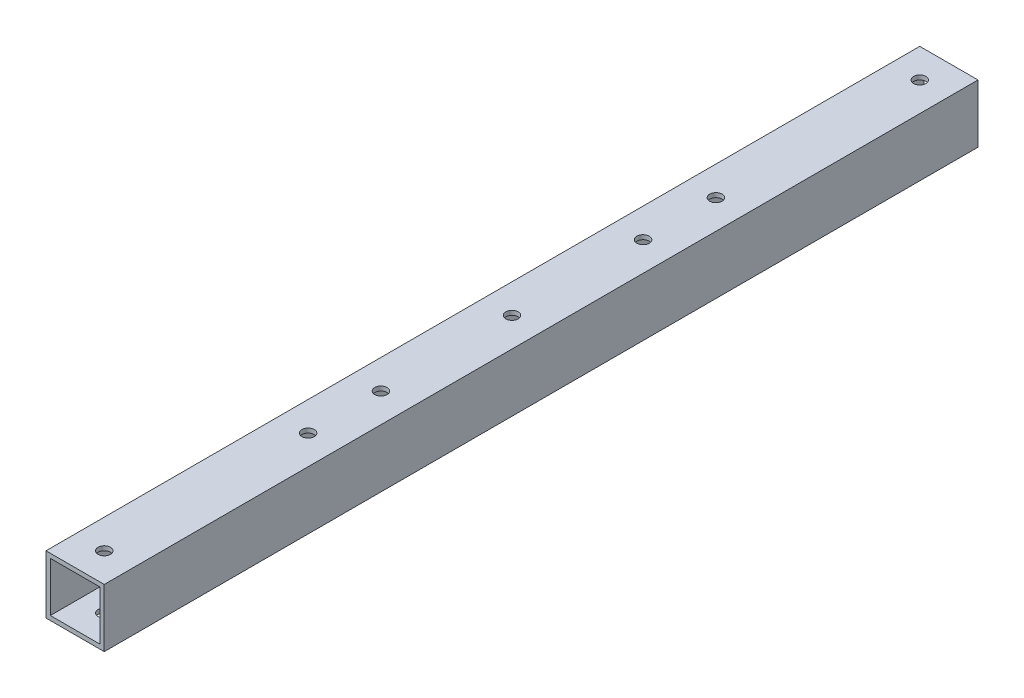
SolidWorks part; units mm, degrees
ref_plane "Front Plane" through (0, 0, 0) normal (0, 0, 1) x (1, 0, 0)
ref_plane "Top Plane" through (0, 0, 0) normal (0, 1, 0) x (1, 0, 0)
ref_plane "Right Plane" through (0, 0, 0) normal (1, 0, 0) x (0, 0, -1)
sketch "Sketch1" plane through (0, 0, 0) normal (0, 0, 1) x (1, 0, 0)
  line L0 (-8.5, -8.5) -> (8.5, -8.5)
  line L1 (-10, -10) -> (10, -10)
  line L2 (-10, -10) -> (-10, 10)
  line L3 (-10, 10) -> (10, 10)
  line L4 (10, -10) -> (10, 10)
  line L5 (-10, -10) -> (10, 10) construction
  line L6 (-10, 10) -> (10, -10) construction
  line L7 (8.5, -8.5) -> (8.5, 8.5)
  line L8 (-8.5, 8.5) -> (8.5, 8.5)
  line L9 (-8.5, -8.5) -> (-8.5, 8.5)
  point P0 (0, 0)
  dimension "D1" = 20
  dimension "D3" = 20
  dimension "D2" = 1.5
extrude "Boss-Extrude1" add sketch "Sketch1" against normal blind 300
sketch "Sketch2" plane through (0, 10, 0) normal (0, 1, 0) x (1, 0, 0)
  line L0 (10, 0) -> (-10, 0) construction
  line L1 (-10, 150) -> (10, 150) construction
  line L2 (-10, 300) -> (-10, 0) construction
  line L3 (10, 300) -> (10, 0) construction
  circle A0 centre (0, 10) radius 2.125
  circle A1 centre (0, 80) radius 2.125
  circle A2 centre (0, 150) radius 2.125
  circle A3 centre (0, 220) radius 2.125
  circle A4 centre (0, 290) radius 2.125
  circle A5 centre (0, 195) radius 2.125
  circle A6 centre (0, 105) radius 2.125
  dimension "D1" = 4.25
  dimension "D5" = 4.25
  dimension "D2" = 10
  dimension "D4" = 70
  dimension "D6" = 25
  dimension "D3" = 5
extrude "Cut-Extrude1" cut sketch "Sketch2" against normal through all
